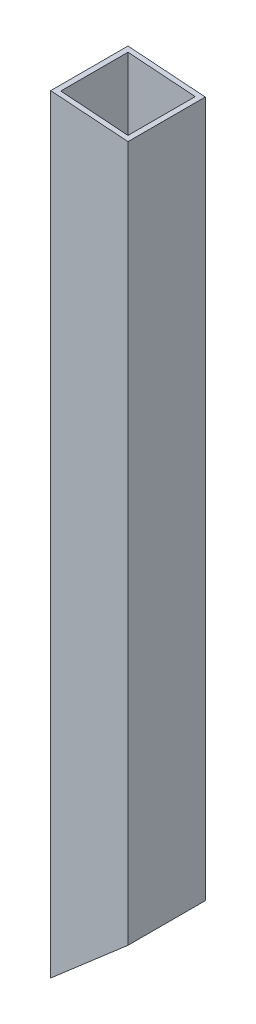
SolidWorks part; units mm, degrees
ref_plane "Front Plane" through (0, 0, 0) normal (0, 0, 1) x (1, 0, 0)
ref_plane "Top Plane" through (0, 0, 0) normal (0, 1, 0) x (1, 0, 0)
ref_plane "Right Plane" through (0, 0, 0) normal (1, 0, 0) x (0, 0, -1)
sketch "Sketch4" plane through (0, 0, 0) normal (0, 1, 0) x (1, 0, 0)
  line L1 (0, 0) -> (25.4, 0)
  line L2 (0, 0) -> (0, 25.4)
  line L3 (0, 25.4) -> (25.4, 25.4)
  line L4 (25.4, 0) -> (25.4, 25.4)
  dimension "D1" = 25.4
  dimension "D2" = 25.4
extrude "Boss-Extrude1" add sketch "Sketch4" along normal blind 252.579
sketch "Sketch5" plane through (0, 0, 0) normal (0, 0, 1) x (1, 0, 0)
  line L1 (0, 252.579) -> (0, 0) construction
  line L4 (0, 252.579) -> (25.4, 252.579)
  line L5 (25.4, 252.579) -> (25.4, 250.7596)
  line L6 (25.4, 252.579) -> (25.4, 0) construction
  line L7 (25.4, 250.7596) -> (0, 252.579)
  line L8 (25.4, 252.579) -> (0, 252.579) construction
  dimension "D1" = 85.903
extrude "Cut-Extrude1" cut sketch "Sketch5" against normal through all
sketch "Sketch6" plane through (0, 0, 0) normal (0, 0, 1) x (1, 0, 0)
  line L0 (0, 0) -> (25.4, 22.0044)
  line L1 (25.4, 250.7596) -> (25.4, 0) construction
  line L2 (25.4, 22.0044) -> (25.4, 0)
  line L3 (25.4, 0) -> (0, 0)
  line L4 (0, 252.579) -> (0, 0) construction
  dimension "D1" = 49.097
extrude "Cut-Extrude2" cut sketch "Sketch6" against normal through all
shell "Shell1" thickness 1.651
equation "\"t2len\"=252.579"
equation "\"D1@Boss-Extrude1\"=\"t2len\""
equation "\"D1@Sketch5\"= ( 180 - atn ( 36 / 250 ) ) / 2"
equation "\"D1@Sketch6\"= ( 180 - atn ( 250 / 36 ) ) / 2"
